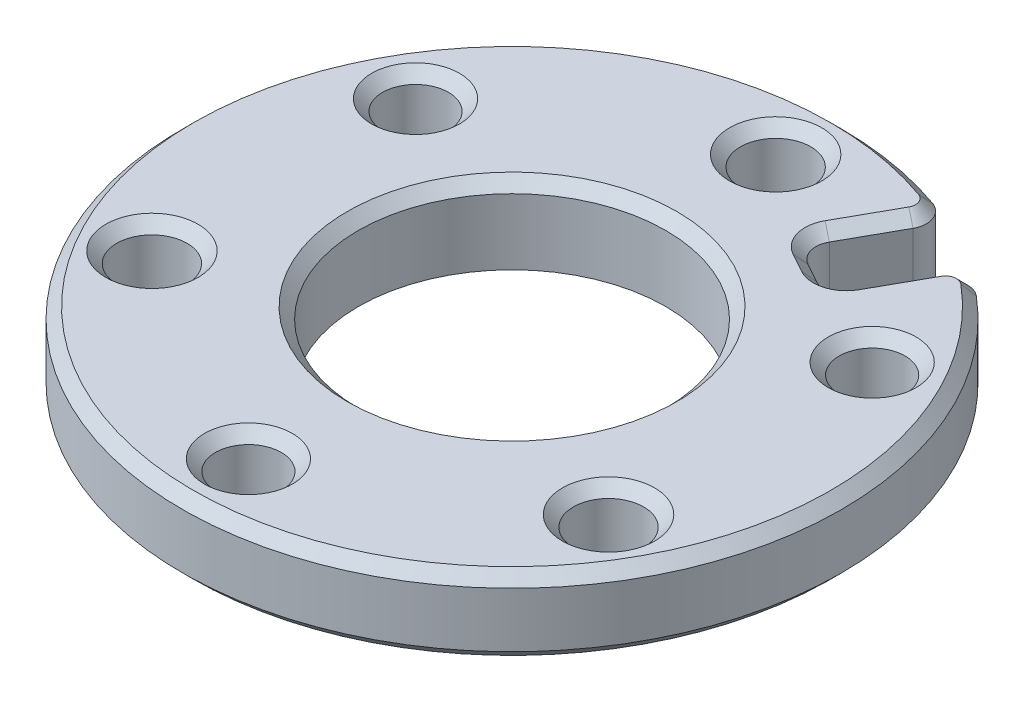
SolidWorks part; units mm, degrees
material "6061 合金"
ref_plane "前视基准面" through (0, 0, 0) normal (0, 0, 1) x (1, 0, 0)
ref_plane "上视基准面" through (0, 0, 0) normal (0, 1, 0) x (1, 0, 0)
ref_plane "右视基准面" through (0, 0, 0) normal (1, 0, 0) x (0, 0, -1)
other "Configuration Table"
sketch "草图1" plane through (0, 0, 0) normal (0, 1, 0) x (1, 0, 0)
  line L0 (0, 0) -> (12, 0) construction
  line L1 (0, 0) -> (10.3923, 6) construction
  circle A0 centre (0, 0) radius 15
  circle A1 centre (0, 0) radius 12 construction
  circle A2 centre (0, 12) radius 1.6
  circle A3 centre (10.3923, -6) radius 1.6
  circle A4 centre (-10.3923, -6) radius 1.6
  circle A5 centre (10.3923, 6) radius 1.5
  circle A6 centre (0, -12) radius 1.5
  circle A7 centre (-10.3923, 6) radius 1.5
  circle A8 centre (0, 0) radius 7
  point P13 (0, 0)
  point P21 (0, 0)
  dimension "D1" = 30
  dimension "D2" = 24
  dimension "D3" = 3.2
  dimension "D5" = 3
  dimension "D6" = 14
  dimension "D8" = 3
  dimension "D4" = 30
  dimension "D7" = 3
extrude "凸台-拉伸1" add sketch "草图1" along normal blind 3.5
sketch "草图2" plane through (0, 3.5, 0) normal (0, 1, 0) x (1, 0, 0)
  line L0 (0, 0) -> (7.5, 12.9904) construction
  line L1 (0, 0) -> (0, 15) construction
  line L2 (3.6903, 9.3915) -> (6.3108, 7.931)
  line L3 (6.3108, 7.931) -> (9.1258, 12.9813)
  line L4 (9.1258, 12.9813) -> (6.5053, 14.4419)
  line L5 (6.5053, 14.4419) -> (3.6903, 9.3915)
  circle A0 centre (0, 0) radius 15 construction
  point P8 (5.0006, 8.6612)
  dimension "D1" = 30
  dimension "D2" = 10
  dimension "D3" = 3
extrude "切除-拉伸1" cut sketch "草图2" against normal blind 8
fillet "圆角1" radius 1 2 edges at (8.7007, 1.75, -12.2187) (6.0951, 1.75, -13.7059)
fillet "圆角2" radius 1 2 edges at (6.3108, 1.75, -7.931) (3.6903, 1.75, -9.3915)
chamfer "倒角1" distance 0.5 angle 45 29 edges at (5.0006, 0, -8.6612) (4.0888, 0, -9.5048) (6.1976, 0, -8.3294) (4.8592, 0, -11.4886) (7.4663, 0, -10.004) (5.6032, 0, -13.5524) (8.8277, 0, -11.7003) (-7.4462, 0, 13.0213) (5.0006, 3.5, -8.6612) (4.0888, 3.5, -9.5048) (6.1976, 3.5, -8.3294) (4.8592, 3.5, -11.4886) (7.4663, 3.5, -10.004) (5.6032, 3.5, -13.5524) (8.8277, 3.5, -11.7003) (-7.4462, 3.5, 13.0213) (-10.3923, 0, 7.6) (0, 0, 13.5) (10.3923, 0, 7.6) (10.3923, 0, -4.5) (0, 0, -10.4) (-10.3923, 0, -4.5) (0, 3.5, -10.4) (10.3923, 3.5, -4.5) (10.3923, 3.5, 7.6) (0, 3.5, 13.5) (-10.3923, 3.5, 7.6) (-10.3923, 3.5, -4.5) (0, 3.5, 7)
